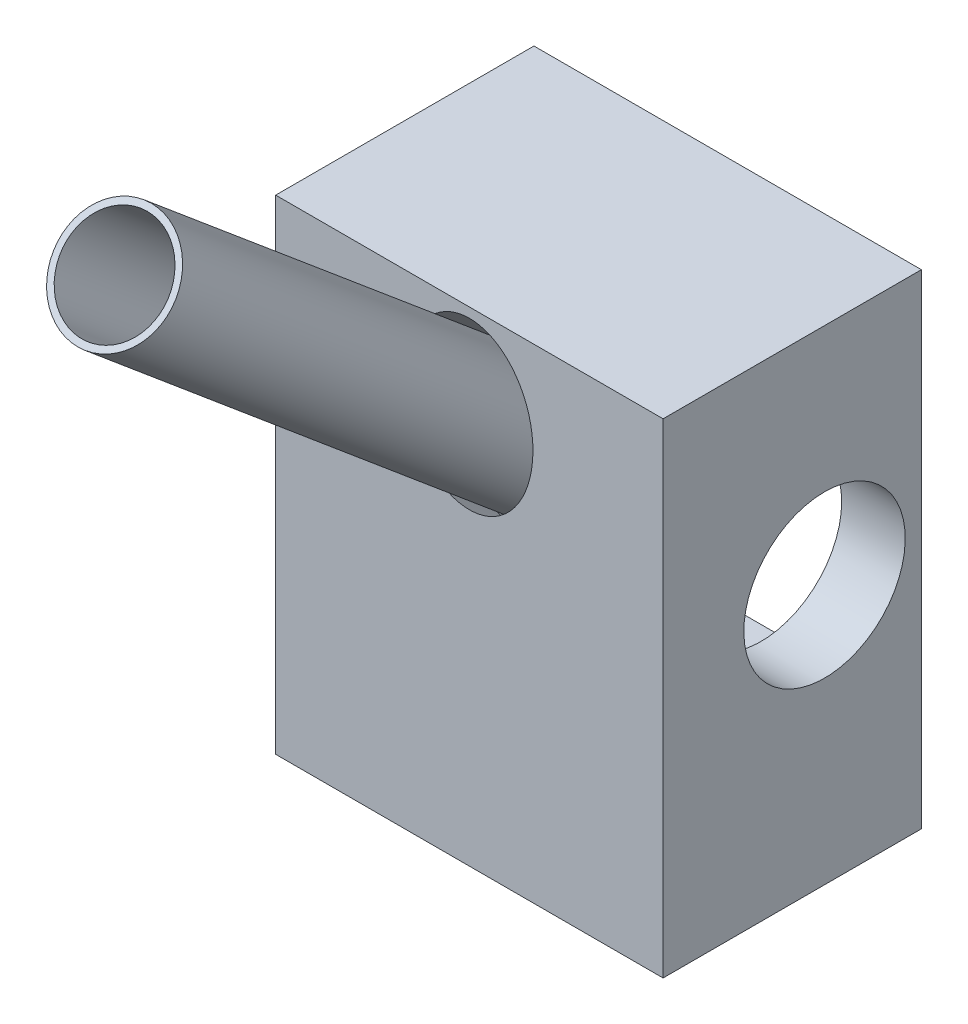
SolidWorks part; units mm, degrees
ref_plane "Front Plane" through (0, 0, 0) normal (0, 0, 1) x (1, 0, 0)
ref_plane "Top Plane" through (0, 0, 0) normal (0, 1, 0) x (1, 0, 0)
ref_plane "Right Plane" through (0, 0, 0) normal (1, 0, 0) x (0, 0, -1)
sketch "Sketch1" plane through (0, 0, 0) normal (0, 0, 1) x (1, 0, 0)
  line L1 (6066.2942, -5703.2258) -> (6096.7742, -5703.2258)
  line L2 (6066.2942, -5703.2258) -> (6066.2942, -5741.3258)
  line L3 (6066.2942, -5741.3258) -> (6096.7742, -5741.3258)
  line L4 (6096.7742, -5703.2258) -> (6096.7742, -5741.3258)
  dimension "D1" = 38.1
  dimension "D2" = 30.48
extrude "Boss-Extrude1" add sketch "Sketch1" along normal blind 20.32 from offset 7.5
sketch "Sketch2" plane through (0, 0, 7.5) normal (0, 0, -1) x (-1, 0, 0)
  line L0 (-6091.7742, -5710.8458) -> (-6096.7742, -5710.8458) construction
  line L1 (-6091.7742, -5710.8458) -> (-6071.3742, -5710.8458)
  line L2 (-6091.7742, -5710.8458) -> (-6091.7742, -5733.7058)
  line L3 (-6091.7742, -5733.7058) -> (-6071.3742, -5733.7058)
  line L4 (-6071.3742, -5710.8458) -> (-6071.3742, -5733.7058)
  line L5 (-6096.7742, -5741.3258) -> (-6096.7742, -5703.2258) construction
  line L6 (-6091.7742, -5710.8458) -> (-6091.7742, -5703.2258) construction
  line L7 (-6096.7742, -5703.2258) -> (-6066.2942, -5703.2258) construction
  line L8 (-6071.3742, -5710.8458) -> (-6066.2942, -5710.8458) construction
  line L9 (-6066.2942, -5703.2258) -> (-6066.2942, -5741.3258) construction
  line L10 (-6091.7742, -5733.7058) -> (-6091.7742, -5741.3258) construction
  line L11 (-6066.2942, -5741.3258) -> (-6096.7742, -5741.3258) construction
  dimension "D1" = 5
  dimension "D2" = 5.08
  dimension "D3" = 7.62
extrude "Cut-Extrude1" cut sketch "Sketch2" against normal blind 16.51
ref_plane "Plane3" through (0, -2342.7368, -2791.965) normal (0, -0.6428, -0.766) x (-1, 0, 0)
sketch "Sketch5" plane through (0, -2342.7368, -2791.965) normal (0, -0.6428, -0.766) x (-1, 0, 0)
  line L0 (-6081.5342, -4392.3948) -> (-6096.7742, -4392.3948) construction
  line L2 (-6081.5342, -4392.3948) -> (-6066.2942, -4392.3948) construction
  line L4 (-6066.2942, -4386.8068) -> (-6066.2942, -4415.9931) construction
  line L5 (-6096.7742, -4415.9931) -> (-6096.7742, -4386.8068) construction
  line L6 (-6081.5342, -4392.3948) -> (-6081.5342, -4386.8068) construction
  line L9 (-6096.7742, -4386.8068) -> (-6066.2942, -4386.8068) construction
  circle A0 centre (-6081.5342, -4392.3948) radius 5
  dimension "D1" = 10
  dimension "D2" = 5.588
extrude "Cut-Extrude2" cut sketch "Sketch5" along normal blind 23
sketch "Sketch10" plane through (0, -2342.7368, -2791.965) normal (0, -0.6428, -0.766) x (-1, 0, 0)
  line L0 (-6081.5342, -4392.3948) -> (-6096.7742, -4392.3948) construction
  line L2 (-6081.5342, -4392.3948) -> (-6066.2942, -4392.3948) construction
  circle A0 centre (-6081.5342, -4392.3948) radius 4.5
  circle A3 centre (-6081.5342, -4392.3948) radius 5 construction
  dimension "D1" = 9
extrude "Boss-Extrude2" add sketch "Sketch10" against normal blind 31.75 and the other way blind 21.59 separate body
sketch "Sketch11" plane through (0, -2356.6146, -2808.5039) normal (0, -0.6428, -0.766) x (1, 0, 0)
  line L0 (6081.5342, 4387.8948) -> (6081.5342, 4392.3948) construction
  line L1 (6086.0342, 4392.3948) -> (6071.072, 4392.3948) construction
  circle A0 centre (6081.5342, 4392.3948) radius 4.5 construction
  circle A1 centre (6081.5342, 4392.3948) radius 4
  dimension "D1" = 8
extrude "Cut-Extrude6" cut sketch "Sketch11" against normal through all
hole_wizard "CSK for M3 Flat Head Machine Screw1" positions "Sketch13" profile "Sketch14" countersink size "M3" standard "ANSI Metric"
sketch "Sketch13" plane through (0, 0, 7.5) normal (0, 0, -1) x (-1, 0, 0)
  line L8 (-6070.1042, -5707.0358) -> (-6070.1042, -5703.2258) construction
  line L9 (-6096.7742, -5703.2258) -> (-6066.2942, -5703.2258) construction
  line L11 (-6070.1042, -5707.0358) -> (-6066.2942, -5707.0358) construction
  line L12 (-6066.2942, -5703.2258) -> (-6066.2942, -5741.3258) construction
  line L14 (-6096.7742, -5707.0358) -> (-6092.9642, -5707.0358) construction
  line L15 (-6096.7742, -5741.3258) -> (-6096.7742, -5703.2258) construction
  line L16 (-6092.9642, -5707.0358) -> (-6092.9642, -5703.2258) construction
  line L18 (-6096.7742, -5737.5158) -> (-6092.9642, -5737.5158) construction
  line L19 (-6092.9642, -5737.5158) -> (-6092.9642, -5741.3258) construction
  line L20 (-6066.2942, -5741.3258) -> (-6096.7742, -5741.3258) construction
  line L22 (-6070.1042, -5737.5158) -> (-6070.1042, -5741.3258) construction
  line L24 (-6070.1042, -5737.5158) -> (-6066.2942, -5737.5158) construction
  point P0 (-6092.9642, -5707.0358)
  point P2 (-6070.1042, -5707.0358)
  point P4 (-6070.1042, -5737.5158)
  point P6 (-6092.9642, -5737.5158)
  point P13 (-6092.9642, -5707.0358)
  dimension "D1" = 3.81
  dimension "D2" = 3.81
sketch "Sketch14" plane through (6092.9642, -5707.0358, 7.5) normal (1, 0, 0) x (0, 1, 0)
  line L0 (0, 0) -> (0, 9.906)
  line L1 (0, 9.906) -> (1.7, 8.8845)
  line L2 (1.7, 8.8845) -> (1.7, 1.45)
  line L3 (1.7, 1.45) -> (3.15, 0)
  line L5 (3.15, 0) -> (0, 0)
  line L6 (-1.7, 1.45) -> (-3.15, 0) construction
  line L10 (0, 9.906) -> (-1.7, 8.8845) construction
  line L11 (0, -6.35) -> (0, 107.95) construction
  dimension "Hole Dia." = 3.4
  dimension "Hole Depth" = 9.906
  dimension "Near C'Sink Dia." = 6.3
  dimension "Near C'Sink Angle" = 90
  dimension "Drill Angle" = 118
sketch "Sketch17" plane through (6096.7742, 0, 0) normal (1, 0, 0) x (0, 0, -1)
  line L0 (-7.5, -5741.3258) -> (-7.5, -5703.2258) construction
  circle A0 centre (-15.12, -5720.8998) radius 6.35
  dimension "D1" = 7.62
  dimension "D2" = 12.7
extrude "Cut-Extrude7" cut sketch "Sketch17" against normal through all
sketch "Sketch19" plane through (0, -5741.3258, 0) normal (0, -1, 0) x (1, 0, 0)
  circle A0 centre (6081.5342, 17.66) radius 0.05
  dimension "D1" = 0.1
extrude "Boss-Extrude3" add sketch "Sketch19" along normal blind 0.1
ref_plane "Plane4" through (6096.7742, -5741.3258, 7.5) normal (0, 1, 0) x (1, 0, 0)
sketch "Sketch29" plane through (0, -5741.3258, 0) normal (0, -1, 0) x (1, 0, 0)
  circle A0 centre (6081.5342, 17.66) radius 6
  dimension "D1" = 12
extrude "Cut-Extrude8" cut sketch "Sketch29" against normal up to surface (7.62 mm away) up to face at (6081.5742, -5733.7058, 15.755)
sketch "Sketch30" plane through (0, -5741.3258, 0) normal (0, -1, 0) x (1, 0, 0)
  line L0 (6072.6442, 11.31) -> (6066.2942, 11.31) construction
  line L1 (6088.5192, 22.867) -> (6092.3292, 22.867)
  line L2 (6088.5192, 22.867) -> (6088.5192, 25.153)
  line L3 (6088.5192, 25.153) -> (6092.3292, 25.153)
  line L4 (6092.3292, 22.867) -> (6092.3292, 25.153)
  line L5 (6088.5192, 22.867) -> (6092.3292, 25.153) construction
  line L6 (6088.5192, 25.153) -> (6092.3292, 22.867) construction
  line L7 (6070.7392, 10.167) -> (6074.5492, 10.167)
  line L8 (6070.7392, 10.167) -> (6070.7392, 12.453)
  line L9 (6070.7392, 12.453) -> (6074.5492, 12.453)
  line L10 (6074.5492, 10.167) -> (6074.5492, 12.453)
  line L11 (6070.7392, 10.167) -> (6074.5492, 12.453) construction
  line L12 (6070.7392, 12.453) -> (6074.5492, 10.167) construction
  line L13 (6066.2942, 27.82) -> (6066.2942, 7.5) construction
  line L14 (6072.6442, 11.31) -> (6072.6442, 7.5) construction
  line L15 (6066.2942, 7.5) -> (6096.7742, 7.5) construction
  line L16 (6090.4242, 24.01) -> (6090.4242, 27.82) construction
  line L17 (6066.2942, 27.82) -> (6096.7742, 27.82) construction
  line L18 (6090.4242, 24.01) -> (6096.7742, 24.01) construction
  line L19 (6096.7742, 27.82) -> (6096.7742, 7.5) construction
  line L20 (6090.4242, 24.01) -> (6090.4242, 11.31) construction
  line L21 (6090.4242, 11.31) -> (6072.6442, 11.31) construction
  point P0 (6090.4242, 24.01)
  point P5 (6072.6442, 11.31)
  dimension "D1" = 3.81
  dimension "D2" = 2.286
  dimension "D3" = 3.81
  dimension "D4" = 2.286
  dimension "D5" = 6.35
  dimension "D6" = 3.81
extrude "Boss-Extrude4" add sketch "Sketch30" along normal blind 2.54
